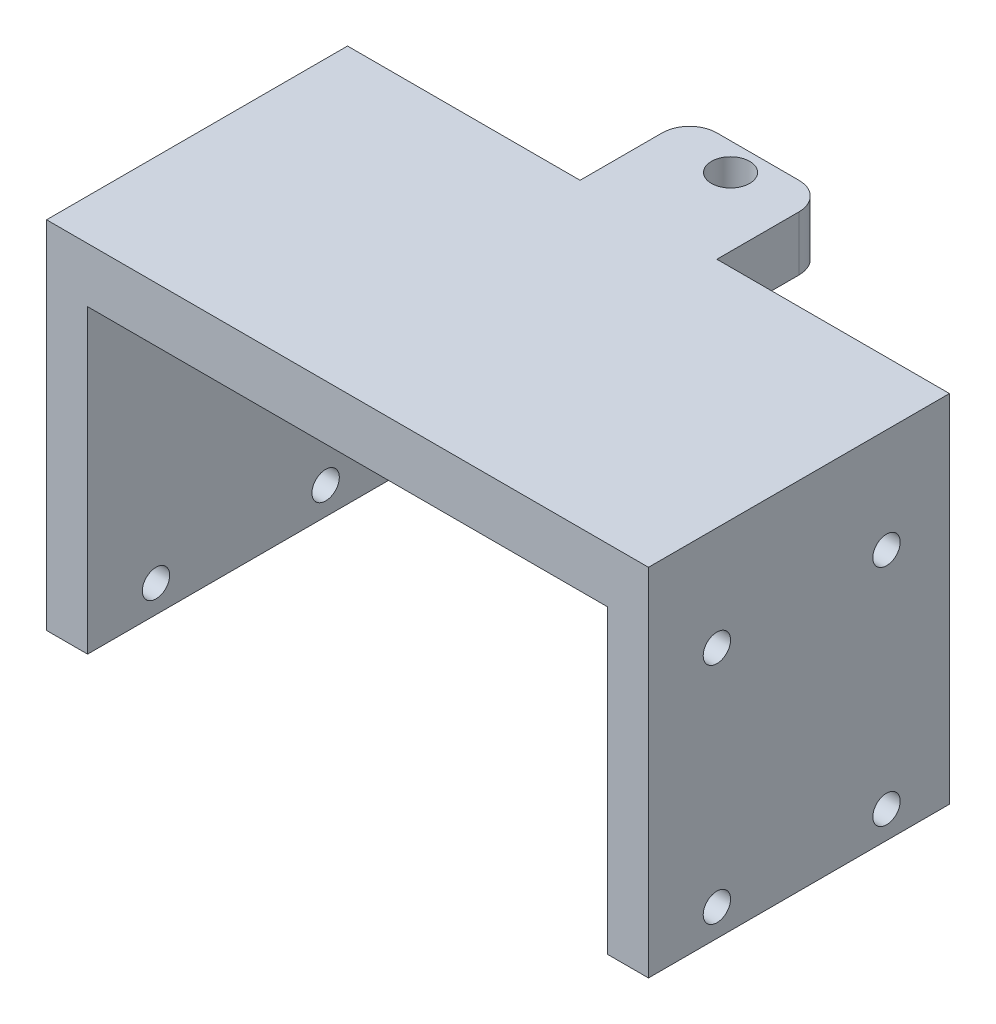
SolidWorks part; units mm, degrees
material "Q235A"
ref_plane "前视" through (0, 0, 0) normal (0, 0, 1) x (1, 0, 0)
ref_plane "上视" through (0, 0, 0) normal (0, 1, 0) x (1, 0, 0)
ref_plane "右视" through (0, 0, 0) normal (1, 0, 0) x (0, 0, -1)
sketch "草图1" plane through (0, 0, 0) normal (0, 0, 1) x (1, 0, 0)
  line L1 (110, -65) -> (-110, -65)
  line L2 (110, -65) -> (110, 65)
  line L3 (110, 65) -> (-110, 65)
  line L4 (-110, -65) -> (-110, 65)
  line L5 (110, -65) -> (-110, 65) construction
  line L6 (110, 65) -> (-110, -65) construction
  point P0 (0, 0)
  dimension "D1" = 130
  dimension "D2" = 220
extrude "凸台-拉伸1" add sketch "草图1" along normal blind 110
sketch "草图2" plane through (0, 0, 110) normal (0, 0, 1) x (1, 0, 0)
  line L0 (-110, -65) -> (110, -65) construction
  line L1 (-95, -65) -> (95, -65)
  line L2 (-95, -65) -> (-95, 45)
  line L3 (-95, 45) -> (95, 45)
  line L4 (95, -65) -> (95, 45)
  line L5 (-110, 65) -> (-110, -65) construction
  line L6 (110, -65) -> (110, 65) construction
  line L7 (110, 65) -> (-110, 65) construction
  dimension "D1" = 15
  dimension "D2" = 15
  dimension "D3" = 20
extrude "切除-拉伸1" cut sketch "草图2" against normal through all
hole_wizard "ST9.5 间隙孔1" positions "草图4" profile "草图3" hole size "ST9.5" standard "GB" end condition through all
sketch "草图4" plane through (-110, 0, 0) normal (-1, 0, 0) x (0, 0, 1)
  line L0 (110, -65) -> (0, -65) construction
  line L1 (110, 65) -> (110, -65) construction
  point P0 (23, 27)
  point P2 (85, 27)
  point P4 (85, -55)
  point P6 (23, -55)
  dimension "D1" = 62
  dimension "D2" = 82
  dimension "D3" = 10
  dimension "D4" = 25
sketch "草图3" plane through (-110, 27, 23) normal (0, 1, 0) x (0, 0, 1)
  line L0 (0, 0) -> (0, 220)
  line L1 (0, 220) -> (5, 220)
  line L2 (5, 220) -> (5, 0)
  line L5 (5, 0) -> (0, 0)
  line L11 (0, -6.35) -> (0, 107.95) construction
  dimension "通孔孔直径" = 10
  dimension "通孔孔深度" = 220
sketch "草图5" plane through (0, 0, 0) normal (0, 0, -1) x (-1, 0, 0)
  line L0 (-110, 65) -> (110, 65) construction
  line L1 (-25, 65) -> (25, 65)
  line L2 (-25, 65) -> (-25, 45)
  line L3 (-25, 45) -> (25, 45)
  line L4 (25, 65) -> (25, 45)
  line L5 (-95, 45) -> (95, 45) construction
  dimension "D1" = 50
  dimension "D2" = 25
extrude "凸台-拉伸2" add sketch "草图5" along normal blind 40
hole_wizard "M16 螺纹孔1" positions "草图7" profile "草图6" tap size "M16" standard "GB" end condition through all
sketch "草图7" plane through (0, 65, 0) normal (0, 1, 0) x (1, 0, 0)
  line L0 (-25, 40) -> (25, 40) construction
  point P0 (0, 30)
  dimension "D1" = 10
sketch "草图6" plane through (0, 65, -30) normal (1, 0, 0) x (0, 0, 1)
  line L0 (0, 0) -> (0, 130)
  line L1 (0, 130) -> (7, 130)
  line L2 (7, 130) -> (7, 0)
  line L5 (7, 0) -> (0, 0)
  line L11 (0, -6.35) -> (0, 107.95) construction
  dimension "通孔螺纹孔钻头直径" = 14
  dimension "通孔螺纹孔钻头深度" = 130
cosmetic thread "孔螺蚊线1" parameters "D2"=16
fillet "圆角1" radius 10 2 edges at (25, 55, -40) (-25, 55, -40)
